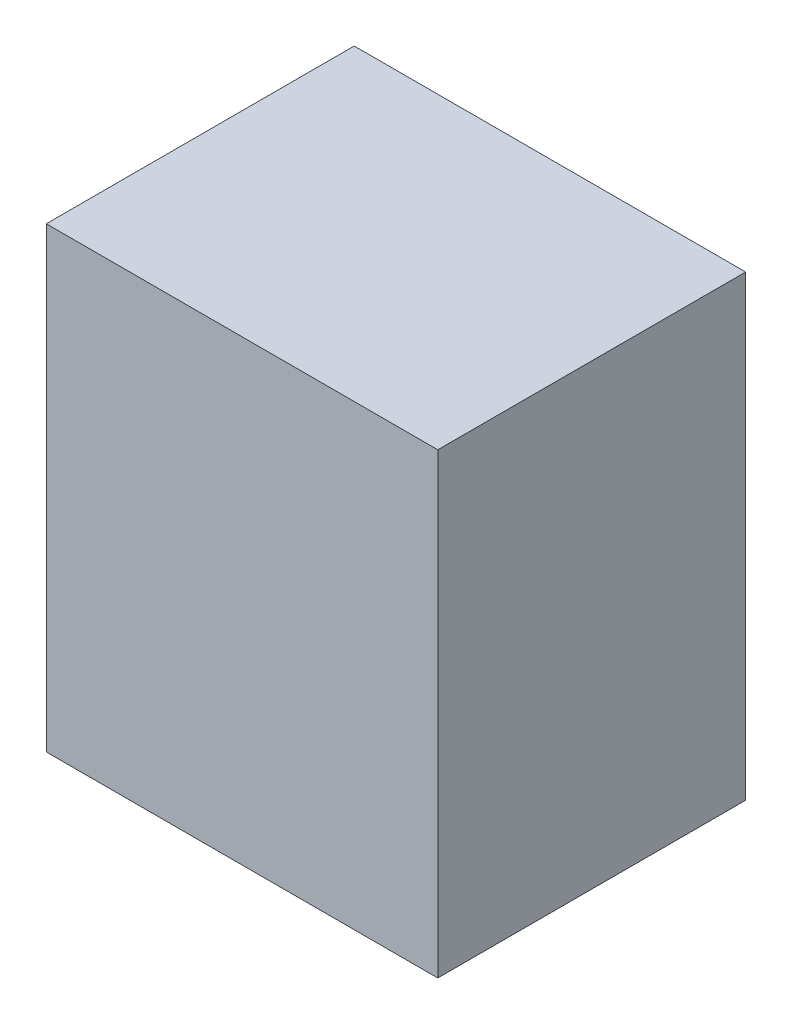
SolidWorks part; units mm, degrees
ref_plane "Płaszczyzna przednia" through (0, 0, 0) normal (0, 0, 1) x (1, 0, 0)
ref_plane "Płaszczyzna górna" through (0, 0, 0) normal (0, 1, 0) x (1, 0, 0)
ref_plane "Płaszczyzna prawa" through (0, 0, 0) normal (1, 0, 0) x (0, 0, -1)
sketch "Szkic6" plane through (0, 0, 0) normal (0, 0, 1) x (-1, 0, 0)
  line L1 (-315.022, 974.5329) -> (-145.022, 974.5329)
  line L2 (-315.022, 974.5329) -> (-315.022, 774.5329)
  line L3 (-315.022, 774.5329) -> (-145.022, 774.5329)
  line L4 (-145.022, 974.5329) -> (-145.022, 774.5329)
  line L7 (-271.682, 774.5329) -> (-279.682, 774.5329)
  dimension "D1" = 170
  dimension "D2" = 200
extrude "Dodanie-wyciągnięcie3" add sketch "Szkic6" along normal blind 4 separate body contours L4 L1 L2 L3
sketch "Szkic7" plane through (0, 0, 0) normal (0, 0, 1) x (-1, 0, 0)
  line L7 (-271.682, 774.5329) -> (-279.682, 774.5329)
  circle A0 centre (-297.4309, 962.0733) radius 1.5
  circle A1 centre (-297.4309, 915.0733) radius 1.5
  circle A2 centre (-162.4309, 915.0733) radius 1.5
  circle A3 centre (-162.4309, 962.0733) radius 1.5
  circle A4 centre (-248.5068, 886.7536) radius 1.5
  circle A5 centre (-221.5068, 886.7536) radius 1.5
  circle A6 centre (-303.022, 855.5729) radius 1
  circle A7 centre (-284.022, 855.5729) radius 1
  circle A8 centre (-305.402, 840.5729) radius 1.6
  circle A9 centre (-277.462, 840.5729) radius 1.6
  circle A10 centre (-310.482, 789.7729) radius 1.6
  circle A11 centre (-262.222, 789.7729) radius 1.6
  circle A12 centre (-237.182, 786.0329) radius 1.5
  circle A13 centre (-216.182, 786.0329) radius 1.5
  circle A14 centre (-193.8213, 805.0329) radius 1.5
  circle A15 centre (-193.8213, 787.0329) radius 1.5
  circle A16 centre (-155.5213, 787.0329) radius 1.5
  circle A17 centre (-155.5213, 805.0329) radius 1.5
  circle A18 centre (-199.022, 818.5329) radius 0.8
  circle A19 centre (-181.022, 818.5329) radius 0.8
  circle A20 centre (-174.022, 818.5329) radius 0.8
  circle A21 centre (-156.022, 818.5329) radius 0.8
  circle A22 centre (-156.022, 896.5329) radius 0.8
  circle A23 centre (-174.022, 896.5329) radius 0.8
  circle A24 centre (-181.022, 896.5329) radius 0.8
  circle A25 centre (-199.022, 896.5329) radius 0.8
  circle A26 centre (-297.4309, 962.0733) radius 5
  circle A27 centre (-297.4309, 915.0733) radius 5
  circle A28 centre (-162.4309, 962.0733) radius 5
  circle A29 centre (-162.4309, 915.0733) radius 5
  circle A30 centre (-199.022, 896.5329) radius 3
  circle A31 centre (-181.022, 896.5329) radius 3
  circle A32 centre (-174.022, 896.5329) radius 3
  circle A33 centre (-156.022, 896.5329) radius 3
  circle A34 centre (-199.022, 818.5329) radius 3
  circle A35 centre (-181.022, 818.5329) radius 3
  circle A36 centre (-174.022, 818.5329) radius 3
  circle A37 centre (-156.022, 818.5329) radius 3
  circle A38 centre (-193.8213, 805.0329) radius 3
  circle A39 centre (-155.5213, 805.0329) radius 3
  circle A40 centre (-193.8213, 787.0329) radius 3
  circle A41 centre (-155.5213, 787.0329) radius 3
  circle A42 centre (-216.182, 786.0329) radius 3
  circle A43 centre (-237.182, 786.0329) radius 3
  circle A44 centre (-262.222, 789.7729) radius 3
  circle A45 centre (-310.482, 789.7729) radius 3
  circle A46 centre (-305.402, 840.5729) radius 3
  circle A47 centre (-277.462, 840.5729) radius 3
  circle A49 centre (-284.022, 855.5729) radius 3
  circle A50 centre (-303.022, 855.5729) radius 3
  circle A51 centre (-248.5068, 886.7536) radius 3
  circle A52 centre (-221.5068, 886.7536) radius 3
  dimension "D1" = 6
  dimension "D2" = 6
  dimension "D3" = 6
  dimension "D4" = 6
  dimension "D5" = 6
  dimension "D6" = 6
  dimension "D7" = 6
  dimension "D8" = 6
  dimension "D9" = 10
  dimension "D10" = 10
  dimension "D11" = 10
  dimension "D12" = 10
extrude "Dodanie-wyciągnięcie4" add sketch "Szkic7" against normal blind 10 contours A28 A3 | A26 A0 | A27 A1 | A51 A4 | A52 A5 | A30 A25 | A31 A24 | A32 A23 | A33 A22 | A29 A2 | A49 A7 | A47 A9 | A50 A6 | A46 A8 | A45 A10 | A44 A11 | A43 A12 | A42 A13 | A34 A18 | A35 A19 | A36 A20 | A37 A21 | A39 A17 | A38 A14 | A40 A15 | A41 A16
sketch "Szkic9" plane through (0, 0, 4) normal (0, 0, 1) x (1, 0, 0)
  line L1 (145.022, -774.5329) -> (315.022, -774.5329)
  line L2 (145.022, -774.5329) -> (145.022, -974.5329)
  line L3 (145.022, -974.5329) -> (315.022, -974.5329)
  line L4 (319.022, -978.5329) -> (319.022, -770.5329)
  line L5 (319.022, -770.5329) -> (141.022, -770.5329)
  line L6 (141.022, -770.5329) -> (141.022, -978.5329)
  line L7 (141.022, -978.5329) -> (319.022, -978.5329)
  line L8 (315.022, -774.5329) -> (315.022, -974.5329)
  dimension "D1" = 208
  dimension "D2" = 178
extrude "Dodanie-wyciągnięcie5" add sketch "Szkic9" against normal blind 140
sketch "Szkic8" plane through (0, 0, 0) normal (0, 0, 1) x (-1, 0, 0)
  line L0 (-279.682, 774.5329) -> (-279.682, 773.5329)
  line L1 (-315.022, 974.5329) -> (-145.022, 974.5329)
  line L2 (-315.022, 974.5329) -> (-315.022, 774.5329)
  line L3 (-315.022, 774.5329) -> (-145.022, 774.5329)
  line L4 (-145.022, 974.5329) -> (-145.022, 774.5329)
  line L5 (-279.682, 773.5329) -> (-271.682, 773.5329)
  line L6 (-271.682, 773.5329) -> (-271.682, 774.5329)
  line L7 (-271.682, 774.5329) -> (-279.682, 774.5329)
  line L8 (-313.022, 774.5329) -> (-313.022, 840.5729)
  line L9 (-313.022, 840.5729) -> (-310.482, 840.5729)
  line L10 (-310.482, 840.5729) -> (-307.482, 843.5729)
  line L11 (-307.482, 843.5729) -> (-273.982, 843.5729)
  line L12 (-273.982, 843.5729) -> (-270.982, 840.5729)
  line L13 (-270.982, 840.5729) -> (-259.682, 840.5729)
  line L14 (-259.682, 840.5729) -> (-259.682, 774.5329)
  line L15 (-239.682, 788.5329) -> (-213.682, 788.5329)
  line L16 (-213.682, 788.5329) -> (-213.682, 779.5329)
  line L17 (-213.682, 779.5329) -> (-239.682, 779.5329)
  line L18 (-239.682, 779.5329) -> (-239.682, 788.5329)
  line L19 (-196.3213, 807.5329) -> (-153.0213, 807.5329)
  line L20 (-153.0213, 807.5329) -> (-153.0213, 784.5329)
  line L21 (-153.0213, 784.5329) -> (-196.3213, 784.5329)
  line L22 (-196.3213, 784.5329) -> (-196.3213, 807.5329)
  line L23 (-200.022, 817.5329) -> (-180.022, 817.5329)
  line L24 (-180.022, 817.5329) -> (-180.022, 897.5329)
  line L25 (-180.022, 897.5329) -> (-200.022, 897.5329)
  line L26 (-200.022, 897.5329) -> (-200.022, 817.5329)
  line L27 (-175.022, 817.5329) -> (-155.022, 817.5329)
  line L28 (-155.022, 817.5329) -> (-155.022, 897.5329)
  line L29 (-155.022, 897.5329) -> (-175.022, 897.5329)
  line L30 (-289.916, 909.8174) -> (-172.916, 909.8174)
  line L31 (-175.022, 897.5329) -> (-175.022, 817.5329)
  line L32 (-250.0068, 896.7536) -> (-220.0068, 896.7536)
  line L33 (-220.0068, 896.7536) -> (-220.0068, 888.2536)
  line L34 (-220.0068, 888.2536) -> (-221.5068, 888.2536)
  line L35 (-221.5068, 888.2536) -> (-221.5068, 885.2536)
  line L36 (-221.5068, 885.2536) -> (-220.0068, 885.2536)
  line L37 (-220.0068, 885.2536) -> (-220.0068, 876.7536)
  line L38 (-220.0068, 876.7536) -> (-250.0068, 876.7536)
  line L39 (-250.0068, 876.7536) -> (-250.0068, 885.2536)
  line L40 (-250.0068, 885.2536) -> (-248.5068, 885.2536)
  line L41 (-248.5068, 885.2536) -> (-248.5068, 888.2536)
  line L42 (-248.5068, 888.2536) -> (-250.0068, 888.2536)
  line L43 (-250.0068, 888.2536) -> (-250.0068, 896.7536)
  line L44 (-305.022, 891.5729) -> (-282.022, 891.5729)
  line L45 (-282.022, 891.5729) -> (-282.022, 853.5729)
  line L46 (-282.022, 853.5729) -> (-305.022, 853.5729)
  line L47 (-305.022, 853.5729) -> (-305.022, 891.5729)
  line L52 (-288.916, 966.785) -> (-173.916, 966.785)
  line L53 (-288.916, 966.785) -> (-288.916, 944.785)
  line L55 (-303.916, 944.785) -> (-303.916, 932.785)
  line L57 (-288.916, 932.785) -> (-288.916, 910.785)
  line L58 (-288.916, 910.785) -> (-173.916, 910.785)
  line L59 (-173.916, 910.785) -> (-173.916, 933.285)
  line L61 (-151.916, 933.285) -> (-151.916, 944.285)
  line L63 (-289.916, 967.785) -> (-172.916, 967.785)
  line L64 (-173.916, 944.285) -> (-173.916, 966.785)
  line L65 (-289.916, 967.785) -> (-289.916, 909.8174)
  line L66 (-288.916, 944.785) -> (-288.916, 932.785)
  line L71 (-173.916, 944.285) -> (-173.916, 933.285)
  line L72 (-172.916, 909.8174) -> (-172.916, 967.785)
  line L73 (-289.916, 932.785) -> (-291.416, 932.785)
  line L74 (-289.916, 944.785) -> (-291.416, 944.785)
  line L75 (-172.916, 933.285) -> (-171.416, 933.285)
  line L76 (-172.916, 944.285) -> (-171.416, 944.285)
  line L77 (-171.416, 909.8174) -> (-171.416, 908.3174)
  line L78 (-171.416, 908.3174) -> (-291.416, 908.3174)
  line L79 (-291.416, 908.3174) -> (-291.416, 969.285)
  line L80 (-291.416, 969.285) -> (-171.416, 969.285)
  line L81 (-171.416, 969.285) -> (-171.416, 908.3174)
  circle A4 centre (-248.5068, 886.7536) radius 1.5
  circle A5 centre (-221.5068, 886.7536) radius 1.5
  circle A6 centre (-303.022, 855.5729) radius 1
  circle A7 centre (-284.022, 855.5729) radius 1
  circle A8 centre (-305.402, 840.5729) radius 1.6
  circle A9 centre (-277.462, 840.5729) radius 1.6
  circle A10 centre (-310.482, 789.7729) radius 1.6
  circle A11 centre (-262.222, 789.7729) radius 1.6
  circle A12 centre (-237.182, 786.0329) radius 1.5
  circle A13 centre (-216.182, 786.0329) radius 1.5
  circle A14 centre (-193.8213, 805.0329) radius 1.5
  circle A15 centre (-193.8213, 787.0329) radius 1.5
  circle A16 centre (-155.5213, 787.0329) radius 1.5
  circle A17 centre (-155.5213, 805.0329) radius 1.5
  circle A18 centre (-199.022, 818.5329) radius 0.8
  circle A19 centre (-181.022, 818.5329) radius 0.8
  circle A20 centre (-174.022, 818.5329) radius 0.8
  circle A21 centre (-156.022, 818.5329) radius 0.8
  circle A22 centre (-156.022, 896.5329) radius 0.8
  circle A23 centre (-174.022, 896.5329) radius 0.8
  circle A24 centre (-181.022, 896.5329) radius 0.8
  circle A25 centre (-199.022, 896.5329) radius 0.8
  dimension "D1" = 170
  dimension "D2" = 200
sketch "Szkic3" plane through (0, 0, 0) normal (0, 0, 1) x (-1, 0, 0)
  line L0 (-279.682, 774.5329) -> (-279.682, 773.5329)
  line L1 (-315.022, 974.5329) -> (-145.022, 974.5329)
  line L2 (-315.022, 974.5329) -> (-315.022, 774.5329)
  line L3 (-315.022, 774.5329) -> (-145.022, 774.5329)
  line L4 (-145.022, 974.5329) -> (-145.022, 774.5329)
  line L5 (-279.682, 773.5329) -> (-271.682, 773.5329)
  line L6 (-271.682, 773.5329) -> (-271.682, 774.5329)
  line L7 (-271.682, 774.5329) -> (-279.682, 774.5329)
  line L8 (-313.022, 774.5329) -> (-313.022, 840.5729)
  line L9 (-313.022, 840.5729) -> (-310.482, 840.5729)
  line L10 (-310.482, 840.5729) -> (-307.482, 843.5729)
  line L11 (-307.482, 843.5729) -> (-273.982, 843.5729)
  line L12 (-273.982, 843.5729) -> (-270.982, 840.5729)
  line L13 (-270.982, 840.5729) -> (-259.682, 840.5729)
  line L14 (-259.682, 840.5729) -> (-259.682, 774.5329)
  line L15 (-239.682, 788.5329) -> (-213.682, 788.5329)
  line L16 (-213.682, 788.5329) -> (-213.682, 779.5329)
  line L17 (-213.682, 779.5329) -> (-239.682, 779.5329)
  line L18 (-239.682, 779.5329) -> (-239.682, 788.5329)
  line L19 (-196.3213, 807.5329) -> (-153.0213, 807.5329)
  line L20 (-153.0213, 807.5329) -> (-153.0213, 784.5329)
  line L21 (-153.0213, 784.5329) -> (-196.3213, 784.5329)
  line L22 (-196.3213, 784.5329) -> (-196.3213, 807.5329)
  line L23 (-200.022, 817.5329) -> (-180.022, 817.5329)
  line L24 (-180.022, 817.5329) -> (-180.022, 897.5329)
  line L25 (-180.022, 897.5329) -> (-200.022, 897.5329)
  line L26 (-200.022, 897.5329) -> (-200.022, 817.5329)
  line L27 (-175.022, 817.5329) -> (-155.022, 817.5329)
  line L28 (-155.022, 817.5329) -> (-155.022, 897.5329)
  line L29 (-155.022, 897.5329) -> (-175.022, 897.5329)
  line L31 (-175.022, 897.5329) -> (-175.022, 817.5329)
  line L32 (-250.0068, 896.7536) -> (-220.0068, 896.7536)
  line L33 (-220.0068, 896.7536) -> (-220.0068, 888.2536)
  line L34 (-220.0068, 888.2536) -> (-221.5068, 888.2536)
  line L35 (-221.5068, 888.2536) -> (-221.5068, 885.2536)
  line L36 (-221.5068, 885.2536) -> (-220.0068, 885.2536)
  line L37 (-220.0068, 885.2536) -> (-220.0068, 876.7536)
  line L38 (-220.0068, 876.7536) -> (-250.0068, 876.7536)
  line L39 (-250.0068, 876.7536) -> (-250.0068, 885.2536)
  line L40 (-250.0068, 885.2536) -> (-248.5068, 885.2536)
  line L41 (-248.5068, 885.2536) -> (-248.5068, 888.2536)
  line L42 (-248.5068, 888.2536) -> (-250.0068, 888.2536)
  line L43 (-250.0068, 888.2536) -> (-250.0068, 896.7536)
  line L44 (-305.022, 891.5729) -> (-282.022, 891.5729)
  line L45 (-282.022, 891.5729) -> (-282.022, 853.5729)
  line L46 (-282.022, 853.5729) -> (-305.022, 853.5729)
  line L47 (-305.022, 853.5729) -> (-305.022, 891.5729)
  line L48 (-299.9309, 964.5733) -> (-159.9309, 964.5733)
  line L49 (-159.9309, 964.5733) -> (-159.9309, 912.5733)
  line L50 (-159.9309, 912.5733) -> (-299.9309, 912.5733)
  line L51 (-299.9309, 912.5733) -> (-299.9309, 964.5733)
  line L52 (-288.916, 966.785) -> (-173.916, 966.785)
  line L53 (-288.916, 966.785) -> (-288.916, 944.785)
  line L54 (-288.916, 944.785) -> (-303.916, 944.785)
  line L55 (-303.916, 944.785) -> (-303.916, 932.785)
  line L56 (-303.916, 932.785) -> (-288.916, 932.785)
  line L57 (-288.916, 932.785) -> (-288.916, 910.785)
  line L58 (-288.916, 910.785) -> (-173.916, 910.785)
  line L59 (-173.916, 910.785) -> (-173.916, 933.285)
  line L60 (-173.916, 933.285) -> (-151.916, 933.285)
  line L61 (-151.916, 933.285) -> (-151.916, 944.285)
  line L62 (-151.916, 944.285) -> (-173.916, 944.285)
  line L64 (-173.916, 944.285) -> (-173.916, 966.785)
  circle A0 centre (-297.4309, 962.0733) radius 1.5
  circle A1 centre (-297.4309, 915.0733) radius 1.5
  circle A2 centre (-162.4309, 915.0733) radius 1.5
  circle A3 centre (-162.4309, 962.0733) radius 1.5
  circle A4 centre (-248.5068, 886.7536) radius 1.5
  circle A5 centre (-221.5068, 886.7536) radius 1.5
  circle A6 centre (-303.022, 855.5729) radius 1
  circle A7 centre (-284.022, 855.5729) radius 1
  circle A8 centre (-305.402, 840.5729) radius 1.6
  circle A9 centre (-277.462, 840.5729) radius 1.6
  circle A10 centre (-310.482, 789.7729) radius 1.6
  circle A11 centre (-262.222, 789.7729) radius 1.6
  circle A12 centre (-237.182, 786.0329) radius 1.5
  circle A13 centre (-216.182, 786.0329) radius 1.5
  circle A14 centre (-193.8213, 805.0329) radius 1.5
  circle A15 centre (-193.8213, 787.0329) radius 1.5
  circle A16 centre (-155.5213, 787.0329) radius 1.5
  circle A17 centre (-155.5213, 805.0329) radius 1.5
  circle A18 centre (-199.022, 818.5329) radius 0.8
  circle A19 centre (-181.022, 818.5329) radius 0.8
  circle A20 centre (-174.022, 818.5329) radius 0.8
  circle A21 centre (-156.022, 818.5329) radius 0.8
  circle A22 centre (-156.022, 896.5329) radius 0.8
  circle A23 centre (-174.022, 896.5329) radius 0.8
  circle A24 centre (-181.022, 896.5329) radius 0.8
  circle A25 centre (-199.022, 896.5329) radius 0.8
  dimension "D1" = 170
  dimension "D2" = 200
extrude "Dodanie-wyciągnięcie7" add sketch "Szkic8" against normal blind 20 contours L81 L80 L79 L74 L65 L63 L72 L76 | L81 L75 L72 L30 L65 L73 L79 L78 L77
sketch "Szkic11" plane through (0, 0, 0) normal (0, 0, -1) x (-1, 0, 0)
  line L0 (-297.4309, -920.0733) -> (-291.416, -920.0733)
  line L1 (-291.416, -908.3174) -> (-291.416, -932.785) construction
  line L2 (-291.416, -920.0733) -> (-291.416, -910.0733)
  line L3 (-291.416, -910.0733) -> (-297.4309, -910.0733)
  line L4 (-297.4309, -967.0733) -> (-291.416, -967.0733)
  line L5 (-291.416, -944.785) -> (-291.416, -969.285) construction
  line L6 (-291.416, -967.0733) -> (-291.416, -957.0733)
  line L7 (-291.416, -957.0733) -> (-297.4309, -957.0733)
  line L8 (-162.4309, -920.0733) -> (-171.416, -920.0733)
  line L9 (-171.416, -933.285) -> (-171.416, -908.3174) construction
  line L10 (-171.416, -920.0733) -> (-171.416, -910.0733)
  line L11 (-171.416, -910.0733) -> (-162.4309, -910.0733)
  line L12 (-162.4309, -967.0733) -> (-171.416, -967.0733)
  line L13 (-171.416, -969.285) -> (-171.416, -944.285) construction
  line L14 (-171.416, -967.0733) -> (-171.416, -957.0733)
  line L15 (-171.416, -957.0733) -> (-162.4309, -957.0733)
  circle A0 centre (-297.4309, -915.0733) radius 1.5
  circle A1 centre (-297.4309, -915.0733) radius 5
  circle A2 centre (-297.4309, -962.0733) radius 1.5
  circle A3 centre (-297.4309, -962.0733) radius 5
  circle A4 centre (-162.4309, -962.0733) radius 1.5
  circle A5 centre (-162.4309, -962.0733) radius 5
  circle A6 centre (-162.4309, -915.0733) radius 1.5
  circle A7 centre (-162.4309, -915.0733) radius 5
  line M1 (-171.416, -944.285) -> (-171.416, -969.285)
  line M3 (-291.416, -969.285) -> (-291.416, -944.785)
  circle M25 centre (-162.4309, -915.0733) radius 5
  circle M32 centre (-297.4309, -915.0733) radius 5
  circle M33 centre (-297.4309, -962.0733) radius 5
  circle M34 centre (-162.4309, -962.0733) radius 5
  line M39 (-171.416, -908.3174) -> (-171.416, -933.285)
  line M45 (-291.416, -932.785) -> (-291.416, -908.3174)
extrude "Dodanie-wyciągnięcie8" add sketch "Szkic11" along normal up to vertex contours L3 L0 M45 M32 | L7 L4 M3 M33 | L11 L8 M39 M25 | L15 L12 M1 M34
sketch "Szkic12" plane through (0, 0, -10) normal (0, 0, -1) x (-1, 0, 0)
  circle A0 centre (-297.4309, -915.0733) radius 1.5
  circle A1 centre (-297.4309, -915.0733) radius 5
  circle A2 centre (-297.4309, -962.0733) radius 1.5
  circle A3 centre (-297.4309, -962.0733) radius 5
  circle A4 centre (-162.4309, -915.0733) radius 1.5
  circle A5 centre (-162.4309, -915.0733) radius 5
  circle A6 centre (-162.4309, -962.0733) radius 1.5
  circle A7 centre (-162.4309, -962.0733) radius 5
extrude "Dodanie-wyciągnięcie9" add sketch "Szkic12" along normal blind 70
sketch "Szkic14" plane through (0, 0, 0) normal (0, 0, -1) x (-1, 0, 0)
  line L0 (-279.682, -774.5329) -> (-279.682, -776.5329)
  line L1 (-279.682, -776.5329) -> (-271.682, -776.5329)
  line L2 (-271.682, -776.5329) -> (-271.682, -774.5329)
  line L3 (-271.682, -774.5329) -> (-279.682, -774.5329)
extrude "Dodanie-wyciągnięcie10" add sketch "Szkic14" along normal blind 70
sketch "Szkic15" plane through (0, 0, 0) normal (0, 0, 1) x (-1, 0, 0)
  line L0 (-279.682, 774.5329) -> (-279.682, 773.5329)
  line L1 (-315.022, 974.5329) -> (-145.022, 974.5329)
  line L2 (-315.022, 974.5329) -> (-315.022, 774.5329)
  line L3 (-315.022, 774.5329) -> (-145.022, 774.5329)
  line L4 (-145.022, 974.5329) -> (-145.022, 774.5329)
  line L5 (-279.682, 773.5329) -> (-271.682, 773.5329)
  line L6 (-271.682, 773.5329) -> (-271.682, 774.5329)
  line L7 (-271.682, 774.5329) -> (-279.682, 774.5329)
  line L8 (-313.022, 774.5329) -> (-313.022, 840.5729)
  line L9 (-313.022, 840.5729) -> (-310.482, 840.5729)
  line L10 (-310.482, 840.5729) -> (-307.482, 843.5729)
  line L11 (-307.482, 843.5729) -> (-273.982, 843.5729)
  line L12 (-273.982, 843.5729) -> (-270.982, 840.5729)
  line L13 (-270.982, 840.5729) -> (-259.682, 840.5729)
  line L14 (-259.682, 840.5729) -> (-259.682, 774.5329)
  line L15 (-239.682, 788.5329) -> (-213.682, 788.5329)
  line L16 (-213.682, 788.5329) -> (-213.682, 779.5329)
  line L17 (-213.682, 779.5329) -> (-239.682, 779.5329)
  line L18 (-239.682, 779.5329) -> (-239.682, 788.5329)
  line L19 (-196.3213, 807.5329) -> (-153.0213, 807.5329)
  line L20 (-153.0213, 807.5329) -> (-153.0213, 784.5329)
  line L21 (-153.0213, 784.5329) -> (-196.3213, 784.5329)
  line L22 (-196.3213, 784.5329) -> (-196.3213, 807.5329)
  line L23 (-200.022, 817.5329) -> (-180.022, 817.5329)
  line L24 (-180.022, 817.5329) -> (-180.022, 897.5329)
  line L25 (-180.022, 897.5329) -> (-200.022, 897.5329)
  line L26 (-200.022, 897.5329) -> (-200.022, 817.5329)
  line L27 (-175.022, 817.5329) -> (-155.022, 817.5329)
  line L28 (-155.022, 817.5329) -> (-155.022, 897.5329)
  line L29 (-155.022, 897.5329) -> (-175.022, 897.5329)
  line L31 (-175.022, 897.5329) -> (-175.022, 817.5329)
  line L32 (-250.0068, 896.7536) -> (-220.0068, 896.7536)
  line L33 (-220.0068, 896.7536) -> (-220.0068, 888.2536)
  line L34 (-220.0068, 888.2536) -> (-221.5068, 888.2536)
  line L35 (-221.5068, 888.2536) -> (-221.5068, 885.2536)
  line L36 (-221.5068, 885.2536) -> (-220.0068, 885.2536)
  line L37 (-220.0068, 885.2536) -> (-220.0068, 876.7536)
  line L38 (-220.0068, 876.7536) -> (-250.0068, 876.7536)
  line L39 (-250.0068, 876.7536) -> (-250.0068, 885.2536)
  line L40 (-250.0068, 885.2536) -> (-248.5068, 885.2536)
  line L41 (-248.5068, 885.2536) -> (-248.5068, 888.2536)
  line L42 (-248.5068, 888.2536) -> (-250.0068, 888.2536)
  line L43 (-250.0068, 888.2536) -> (-250.0068, 896.7536)
  line L44 (-305.022, 891.5729) -> (-282.022, 891.5729)
  line L45 (-282.022, 891.5729) -> (-282.022, 853.5729)
  line L46 (-282.022, 853.5729) -> (-305.022, 853.5729)
  line L47 (-305.022, 853.5729) -> (-305.022, 891.5729)
  line L48 (-299.9309, 964.5733) -> (-159.9309, 964.5733)
  line L49 (-159.9309, 964.5733) -> (-159.9309, 912.5733)
  line L50 (-159.9309, 912.5733) -> (-299.9309, 912.5733)
  line L51 (-299.9309, 912.5733) -> (-299.9309, 964.5733)
  line L52 (-288.916, 966.785) -> (-173.916, 966.785)
  line L53 (-288.916, 966.785) -> (-288.916, 944.785)
  line L54 (-288.916, 944.785) -> (-303.916, 944.785)
  line L55 (-303.916, 944.785) -> (-303.916, 932.785)
  line L56 (-303.916, 932.785) -> (-288.916, 932.785)
  line L57 (-288.916, 932.785) -> (-288.916, 910.785)
  line L58 (-288.916, 910.785) -> (-173.916, 910.785)
  line L59 (-173.916, 910.785) -> (-173.916, 933.285)
  line L60 (-173.916, 933.285) -> (-151.916, 933.285)
  line L61 (-151.916, 933.285) -> (-151.916, 944.285)
  line L62 (-151.916, 944.285) -> (-173.916, 944.285)
  line L64 (-173.916, 944.285) -> (-173.916, 966.785)
  circle A0 centre (-297.4309, 962.0733) radius 1.5
  circle A1 centre (-297.4309, 915.0733) radius 1.5
  circle A2 centre (-162.4309, 915.0733) radius 1.5
  circle A3 centre (-162.4309, 962.0733) radius 1.5
  circle A4 centre (-248.5068, 886.7536) radius 1.5
  circle A5 centre (-221.5068, 886.7536) radius 1.5
  circle A6 centre (-303.022, 855.5729) radius 1
  circle A7 centre (-284.022, 855.5729) radius 1
  circle A8 centre (-305.402, 840.5729) radius 1.6
  circle A9 centre (-277.462, 840.5729) radius 1.6
  circle A10 centre (-310.482, 789.7729) radius 1.6
  circle A11 centre (-262.222, 789.7729) radius 1.6
  circle A12 centre (-237.182, 786.0329) radius 1.5
  circle A13 centre (-216.182, 786.0329) radius 1.5
  circle A14 centre (-193.8213, 805.0329) radius 1.5
  circle A15 centre (-193.8213, 787.0329) radius 1.5
  circle A16 centre (-155.5213, 787.0329) radius 1.5
  circle A17 centre (-155.5213, 805.0329) radius 1.5
  circle A18 centre (-199.022, 818.5329) radius 0.8
  circle A19 centre (-181.022, 818.5329) radius 0.8
  circle A20 centre (-174.022, 818.5329) radius 0.8
  circle A21 centre (-156.022, 818.5329) radius 0.8
  circle A22 centre (-156.022, 896.5329) radius 0.8
  circle A23 centre (-174.022, 896.5329) radius 0.8
  circle A24 centre (-181.022, 896.5329) radius 0.8
  circle A25 centre (-199.022, 896.5329) radius 0.8
  dimension "D1" = 170
  dimension "D2" = 200
